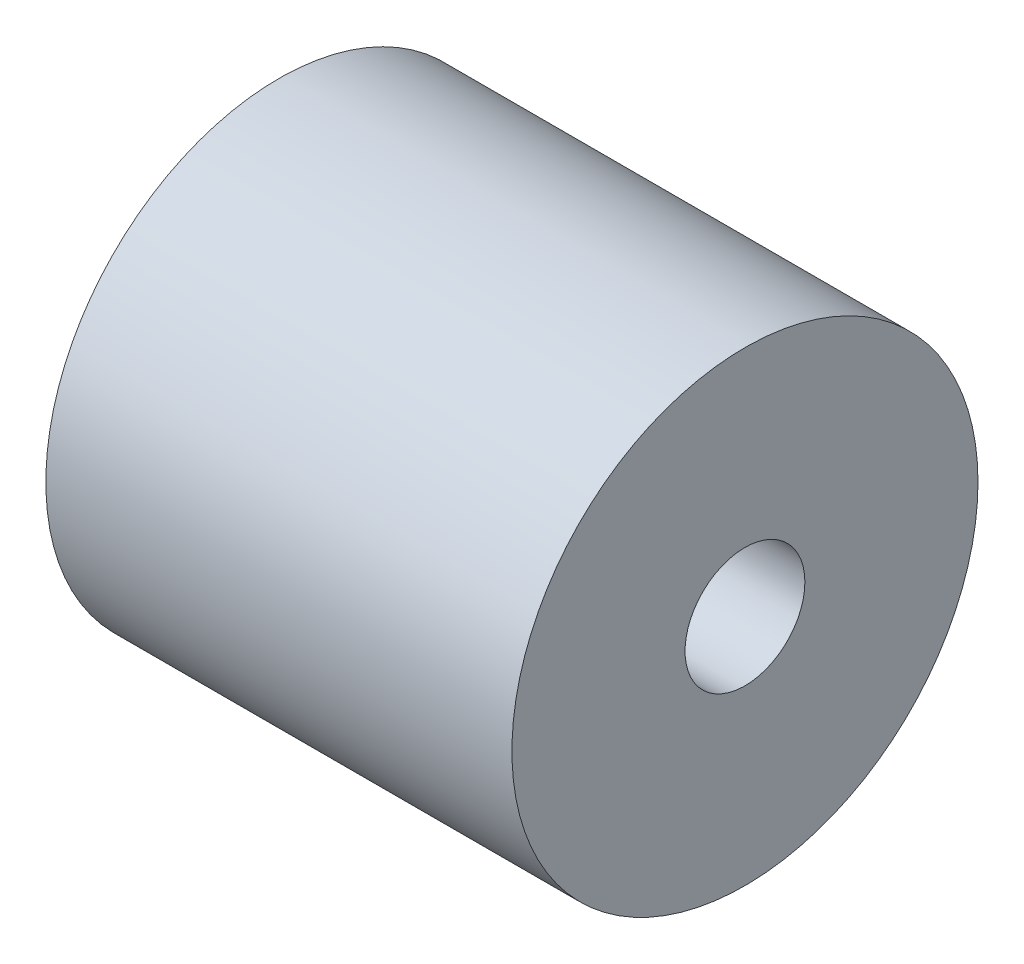
SolidWorks part; units mm, degrees
ref_plane "Front Plane" through (0, 0, 0) normal (0, 0, 1) x (1, 0, 0)
ref_plane "Top Plane" through (0, 0, 0) normal (0, 1, 0) x (1, 0, 0)
ref_plane "Right Plane" through (0, 0, 0) normal (1, 0, 0) x (0, 0, -1)
sketch "Sketch1" plane through (0, 0, 0) normal (1, 0, 0) x (0, 0, -1)
  circle A0 centre (0, 0) radius 1.8
  circle A1 centre (0, 0) radius 7
  dimension "D1" = 3.6
  dimension "D2" = 14
extrude "Boss-Extrude1" add sketch "Sketch1" along normal blind 14
